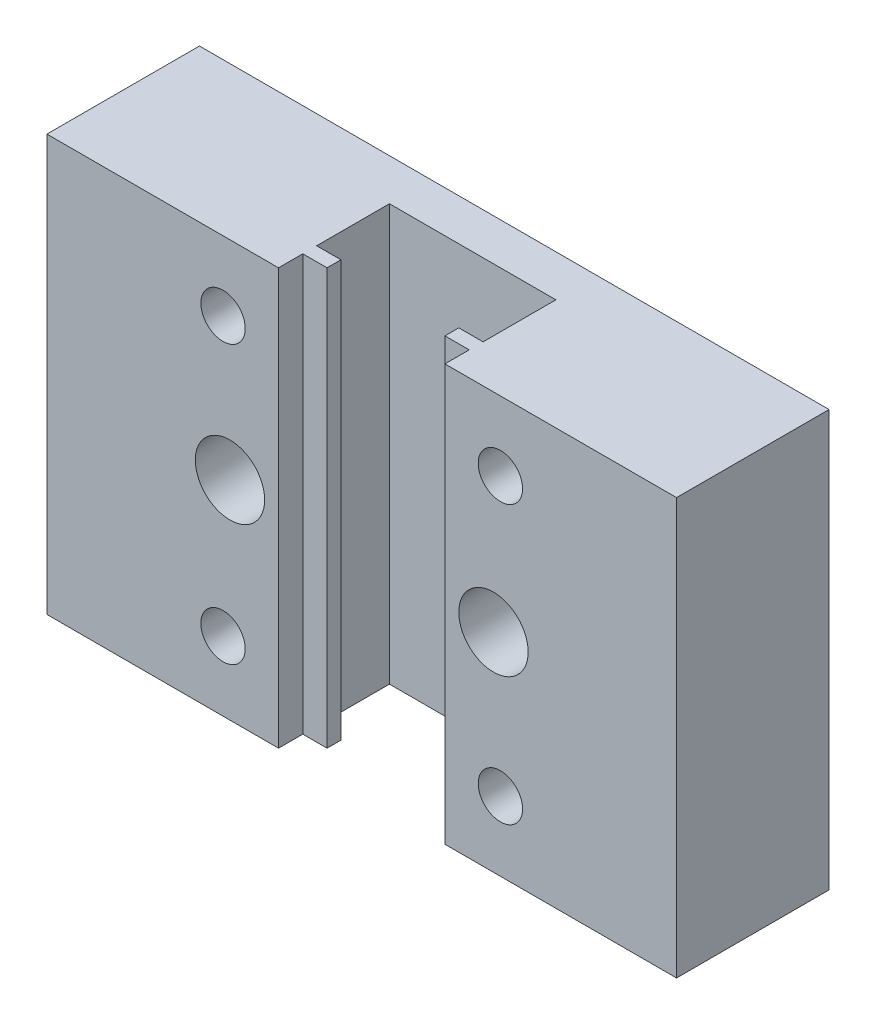
SolidWorks part; units mm, degrees
ref_plane "Front Plane" through (0, 0, 0) normal (0, 0, 1) x (1, 0, 0)
ref_plane "Top Plane" through (0, 0, 0) normal (0, 1, 0) x (1, 0, 0)
ref_plane "Right Plane" through (0, 0, 0) normal (1, 0, 0) x (0, 0, -1)
sketch "Sketch1" plane through (0, 0, 0) normal (0, 1, 0) x (1, 0, 0)
  line L0 (-6, -1.25) -> (-4.25, -1.25)
  line L2 (-22.7, -4) -> (-22.7, 7)
  line L3 (-22.7, 7) -> (22.7, 7)
  line L4 (22.7, -4) -> (22.7, 7)
  line L5 (-22.7, -7) -> (22.7, 7) construction
  line L6 (-22.7, 7) -> (22.7, -7) construction
  line L8 (-6, -4) -> (-6, -2.25)
  line L9 (-6, 4) -> (6, 4)
  line L10 (6, -4) -> (6, -2.25)
  line L11 (-6, -4) -> (6, 4) construction
  line L12 (-6, 4) -> (6, -4) construction
  line L13 (-4.25, -1.25) -> (-4.25, -2.25)
  line L14 (-4.25, -2.25) -> (-6, -2.25)
  line L15 (0, 4) -> (0, -4) construction
  line L16 (4.25, -2.25) -> (6, -2.25)
  line L17 (4.25, -1.25) -> (4.25, -2.25)
  line L18 (6, -1.25) -> (4.25, -1.25)
  line L19 (-6, -1.25) -> (-6, 4)
  line L20 (6, -1.25) -> (6, 4)
  line L21 (-6, -4) -> (-22.7, -4)
  line L22 (6, -4) -> (22.7, -4)
  point P0 (0, 0)
  point P6 (0, 0)
  dimension "D1" = 14
  dimension "D2" = 45.4
  dimension "D3" = 12
  dimension "D4" = 8
  dimension "D6" = 16.7
  dimension "D8" = 1.75
  dimension "D9" = 1
extrude "Boss-Extrude1" add sketch "Sketch1" along normal blind 30
hole_wizard "Ø3.0mm Dowel Hole1" positions "Sketch4" profile "Sketch5" hole size "Ø3.0" standard "ANSI Metric" end condition through all
sketch "Sketch4" plane through (0, 0, 4) normal (0, 0, 1) x (1, 0, 0)
  point P0 (-10, 25)
  point P6 (10, 25)
  point P7 (10, 5)
  point P8 (-10, 5)
  dimension "D1" = 2
  dimension "D2" = 2
sketch "Sketch5" plane through (-10, 25, 4) normal (1, 0, 0) x (0, -1, 0)
  line L0 (0, 0) -> (0, 11)
  line L1 (0, 11) -> (1.6, 11)
  line L2 (1.6, 11) -> (1.6, 0)
  line L5 (1.6, 0) -> (0, 0)
  line L11 (0, -6.35) -> (0, 107.95) construction
  dimension "Thru Hole Dia." = 3.2
  dimension "Thru Hole Depth" = 11
sketch "Sketch6" plane through (0, 0, 4) normal (0, 0, 1) x (1, 0, 0)
  line L0 (22.7, 30) -> (22.7, 0) construction
  line L2 (-22.7, 30) -> (-22.7, 0) construction
  line L3 (-22.7, 30) -> (-6, 30) construction
  line L4 (6, 30) -> (22.7, 30) construction
  circle A0 centre (9.5, 15) radius 2.5
  circle A1 centre (-9.5, 15) radius 2.5
  dimension "D1" = 5
  dimension "D2" = 13.2
  dimension "D3" = 5
  dimension "D4" = 13.2
  dimension "D5" = 15
  dimension "D6" = 15
extrude "Cut-Extrude1" cut sketch "Sketch6" against normal blind 8
